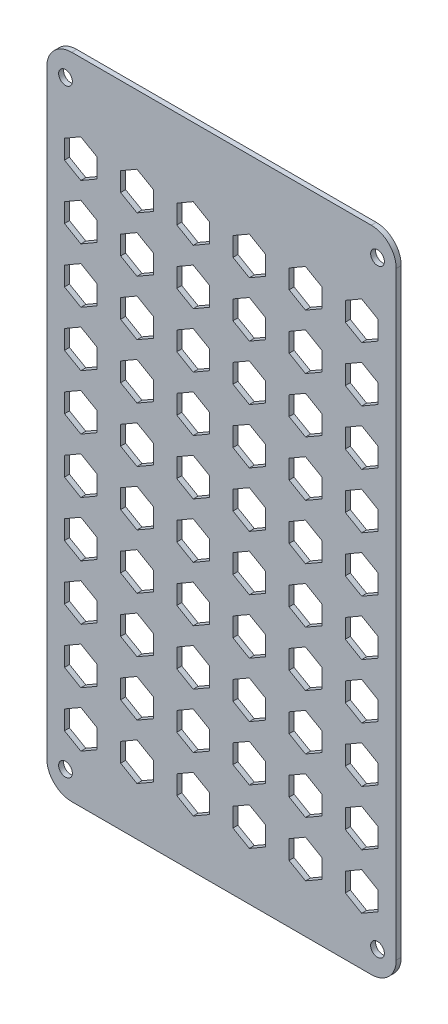
SolidWorks part; units mm, degrees
ref_plane "Front Plane" through (0, 0, 0) normal (0, 0, 1) x (1, 0, 0)
ref_plane "Top Plane" through (0, 0, 0) normal (0, 1, 0) x (1, 0, 0)
ref_plane "Right Plane" through (0, 0, 0) normal (1, 0, 0) x (0, 0, -1)
sketch "Sketch1" plane through (0, 0, 0) normal (0, 0, 1) x (1, 0, 0)
  line L1 (70, -130) -> (-70, -130)
  line L2 (70, -130) -> (70, 130)
  line L3 (70, 130) -> (-70, 130)
  line L4 (-70, -130) -> (-70, 130)
  line L5 (70, -130) -> (-70, 130) construction
  line L6 (70, 130) -> (-70, -130) construction
  point P0 (0, 0)
  dimension "D1" = 260
  dimension "D2" = 140
extrude "Boss-Extrude1" add sketch "Sketch1" along normal blind 2
sketch "Sketch2" plane through (0, 0, 2) normal (0, 0, 1) x (1, 0, 0)
  line L1 (62.5, -120) -> (-62.5, -120)
  line L2 (62.5, -120) -> (62.5, 120)
  line L3 (62.5, 120) -> (-62.5, 120)
  line L4 (-62.5, -120) -> (-62.5, 120)
  line L5 (62.5, -120) -> (-62.5, 120) construction
  line L6 (62.5, 120) -> (-62.5, -120) construction
  point P0 (0, 0)
  dimension "D1" = 125
  dimension "D2" = 240
hole_wizard "M5 Clearance Hole1" positions "3DSketch1" profile "Sketch3" hole size "M5" standard "ISO" end condition through all
sketch3d "3DSketch1"
  point P0 (-62.5, 120, 2)
  point P3 (62.5, 120, 2)
  point P6 (62.5, -120, 2)
  point P9 (-62.5, -120, 2)
sketch "Sketch3" plane through (-62.5, 120, 2) normal (1, 0, 0) x (0, -1, 0)
  line L0 (0, 0) -> (0, 2)
  line L1 (0, 2) -> (2.75, 2)
  line L2 (2.75, 2) -> (2.75, 0)
  line L5 (2.75, 0) -> (0, 0)
  line L11 (0, -6.35) -> (0, 107.95) construction
  dimension "Thru Hole Dia." = 5.5
  dimension "Thru Hole Depth" = 2
fillet "Fillet1" radius 10 4 edges at (-70, -130, 1) (70, -130, 1) (70, 130, 1) (-70, 130, 1)
sketch "Sketch4" plane through (0, 0, 2) normal (0, 0, 1) x (1, 0, 0)
  line L0 (-33.8527, 102.5023) -> (-40.4144, 98.7139)
  line L1 (-56.3527, 102.5023) -> (-62.9144, 98.7139)
  line L2 (-62.9144, 98.7139) -> (-62.9144, 91.1371)
  line L3 (-62.9144, 91.1371) -> (-56.3527, 87.3487)
  line L4 (-56.3527, 87.3487) -> (-49.791, 91.1371)
  line L5 (-49.791, 91.1371) -> (-49.791, 98.7139)
  line L6 (-49.791, 98.7139) -> (-56.3527, 102.5023)
  line L7 (-40.4144, 98.7139) -> (-40.4144, 91.1371)
  line L8 (-40.4144, 91.1371) -> (-33.8527, 87.3487)
  line L9 (-33.8527, 87.3487) -> (-27.291, 91.1371)
  line L10 (-27.291, 91.1371) -> (-27.291, 98.7139)
  line L11 (-27.291, 98.7139) -> (-33.8527, 102.5023)
  line L12 (-11.3527, 102.5023) -> (-17.9144, 98.7139)
  line L13 (-17.9144, 98.7139) -> (-17.9144, 91.1371)
  line L14 (-17.9144, 91.1371) -> (-11.3527, 87.3487)
  line L15 (-11.3527, 87.3487) -> (-4.791, 91.1371)
  line L16 (-4.791, 91.1371) -> (-4.791, 98.7139)
  line L17 (-4.791, 98.7139) -> (-11.3527, 102.5023)
  line L18 (11.1473, 102.5023) -> (4.5856, 98.7139)
  line L19 (4.5856, 98.7139) -> (4.5856, 91.1371)
  line L20 (4.5856, 91.1371) -> (11.1473, 87.3487)
  line L21 (11.1473, 87.3487) -> (17.709, 91.1371)
  line L22 (17.709, 91.1371) -> (17.709, 98.7139)
  line L23 (17.709, 98.7139) -> (11.1473, 102.5023)
  line L24 (33.6473, 102.5023) -> (27.0856, 98.7139)
  line L25 (27.0856, 98.7139) -> (27.0856, 91.1371)
  line L26 (27.0856, 91.1371) -> (33.6473, 87.3487)
  line L27 (33.6473, 87.3487) -> (40.209, 91.1371)
  line L28 (40.209, 91.1371) -> (40.209, 98.7139)
  line L29 (40.209, 98.7139) -> (33.6473, 102.5023)
  line L30 (56.1473, 102.5023) -> (49.5856, 98.7139)
  line L31 (49.5856, 98.7139) -> (49.5856, 91.1371)
  line L32 (49.5856, 91.1371) -> (56.1473, 87.3487)
  line L33 (56.1473, 87.3487) -> (62.709, 91.1371)
  line L34 (62.709, 91.1371) -> (62.709, 98.7139)
  line L35 (62.709, 98.7139) -> (56.1473, 102.5023)
  line L36 (-33.8527, 80.5023) -> (-40.4144, 76.7139)
  line L37 (-40.4144, 76.7139) -> (-40.4144, 69.1371)
  line L38 (-40.4144, 69.1371) -> (-33.8527, 65.3487)
  line L39 (-33.8527, 65.3487) -> (-27.291, 69.1371)
  line L40 (-27.291, 69.1371) -> (-27.291, 76.7139)
  line L41 (-27.291, 76.7139) -> (-33.8527, 80.5023)
  line L42 (-11.3527, 80.5023) -> (-17.9144, 76.7139)
  line L43 (-17.9144, 76.7139) -> (-17.9144, 69.1371)
  line L44 (-17.9144, 69.1371) -> (-11.3527, 65.3487)
  line L45 (-11.3527, 65.3487) -> (-4.791, 69.1371)
  line L46 (-4.791, 69.1371) -> (-4.791, 76.7139)
  line L47 (-4.791, 76.7139) -> (-11.3527, 80.5023)
  line L48 (11.1473, 80.5023) -> (4.5856, 76.7139)
  line L49 (4.5856, 76.7139) -> (4.5856, 69.1371)
  line L50 (4.5856, 69.1371) -> (11.1473, 65.3487)
  line L51 (11.1473, 65.3487) -> (17.709, 69.1371)
  line L52 (17.709, 69.1371) -> (17.709, 76.7139)
  line L53 (17.709, 76.7139) -> (11.1473, 80.5023)
  line L54 (33.6473, 80.5023) -> (27.0856, 76.7139)
  line L55 (27.0856, 76.7139) -> (27.0856, 69.1371)
  line L56 (27.0856, 69.1371) -> (33.6473, 65.3487)
  line L57 (33.6473, 65.3487) -> (40.209, 69.1371)
  line L58 (40.209, 69.1371) -> (40.209, 76.7139)
  line L59 (40.209, 76.7139) -> (33.6473, 80.5023)
  line L60 (56.1473, 80.5023) -> (49.5856, 76.7139)
  line L61 (49.5856, 76.7139) -> (49.5856, 69.1371)
  line L62 (49.5856, 69.1371) -> (56.1473, 65.3487)
  line L63 (56.1473, 65.3487) -> (62.709, 69.1371)
  line L64 (62.709, 69.1371) -> (62.709, 76.7139)
  line L65 (62.709, 76.7139) -> (56.1473, 80.5023)
  line L66 (-33.8527, 58.5023) -> (-40.4144, 54.7139)
  line L67 (-40.4144, 54.7139) -> (-40.4144, 47.1371)
  line L68 (-40.4144, 47.1371) -> (-33.8527, 43.3487)
  line L69 (-33.8527, 43.3487) -> (-27.291, 47.1371)
  line L70 (-27.291, 47.1371) -> (-27.291, 54.7139)
  line L71 (-27.291, 54.7139) -> (-33.8527, 58.5023)
  line L72 (-11.3527, 58.5023) -> (-17.9144, 54.7139)
  line L73 (-17.9144, 54.7139) -> (-17.9144, 47.1371)
  line L74 (-17.9144, 47.1371) -> (-11.3527, 43.3487)
  line L75 (-11.3527, 43.3487) -> (-4.791, 47.1371)
  line L76 (-4.791, 47.1371) -> (-4.791, 54.7139)
  line L77 (-4.791, 54.7139) -> (-11.3527, 58.5023)
  line L78 (11.1473, 58.5023) -> (4.5856, 54.7139)
  line L79 (4.5856, 54.7139) -> (4.5856, 47.1371)
  line L80 (4.5856, 47.1371) -> (11.1473, 43.3487)
  line L81 (11.1473, 43.3487) -> (17.709, 47.1371)
  line L82 (17.709, 47.1371) -> (17.709, 54.7139)
  line L83 (17.709, 54.7139) -> (11.1473, 58.5023)
  line L84 (33.6473, 58.5023) -> (27.0856, 54.7139)
  line L85 (27.0856, 54.7139) -> (27.0856, 47.1371)
  line L86 (27.0856, 47.1371) -> (33.6473, 43.3487)
  line L87 (33.6473, 43.3487) -> (40.209, 47.1371)
  line L88 (40.209, 47.1371) -> (40.209, 54.7139)
  line L89 (40.209, 54.7139) -> (33.6473, 58.5023)
  line L90 (56.1473, 58.5023) -> (49.5856, 54.7139)
  line L91 (49.5856, 54.7139) -> (49.5856, 47.1371)
  line L92 (49.5856, 47.1371) -> (56.1473, 43.3487)
  line L93 (56.1473, 43.3487) -> (62.709, 47.1371)
  line L94 (62.709, 47.1371) -> (62.709, 54.7139)
  line L95 (62.709, 54.7139) -> (56.1473, 58.5023)
  line L96 (-33.8527, 36.5023) -> (-40.4144, 32.7139)
  line L97 (-40.4144, 32.7139) -> (-40.4144, 25.1371)
  line L98 (-40.4144, 25.1371) -> (-33.8527, 21.3487)
  line L99 (-33.8527, 21.3487) -> (-27.291, 25.1371)
  line L100 (-27.291, 25.1371) -> (-27.291, 32.7139)
  line L101 (-27.291, 32.7139) -> (-33.8527, 36.5023)
  line L102 (-11.3527, 36.5023) -> (-17.9144, 32.7139)
  line L103 (-17.9144, 32.7139) -> (-17.9144, 25.1371)
  line L104 (-17.9144, 25.1371) -> (-11.3527, 21.3487)
  line L105 (-11.3527, 21.3487) -> (-4.791, 25.1371)
  line L106 (-4.791, 25.1371) -> (-4.791, 32.7139)
  line L107 (-4.791, 32.7139) -> (-11.3527, 36.5023)
  line L108 (11.1473, 36.5023) -> (4.5856, 32.7139)
  line L109 (4.5856, 32.7139) -> (4.5856, 25.1371)
  line L110 (4.5856, 25.1371) -> (11.1473, 21.3487)
  line L111 (11.1473, 21.3487) -> (17.709, 25.1371)
  line L112 (17.709, 25.1371) -> (17.709, 32.7139)
  line L113 (17.709, 32.7139) -> (11.1473, 36.5023)
  line L114 (33.6473, 36.5023) -> (27.0856, 32.7139)
  line L115 (27.0856, 32.7139) -> (27.0856, 25.1371)
  line L116 (27.0856, 25.1371) -> (33.6473, 21.3487)
  line L117 (33.6473, 21.3487) -> (40.209, 25.1371)
  line L118 (40.209, 25.1371) -> (40.209, 32.7139)
  line L119 (40.209, 32.7139) -> (33.6473, 36.5023)
  line L120 (56.1473, 36.5023) -> (49.5856, 32.7139)
  line L121 (49.5856, 32.7139) -> (49.5856, 25.1371)
  line L122 (49.5856, 25.1371) -> (56.1473, 21.3487)
  line L123 (56.1473, 21.3487) -> (62.709, 25.1371)
  line L124 (62.709, 25.1371) -> (62.709, 32.7139)
  line L125 (62.709, 32.7139) -> (56.1473, 36.5023)
  line L126 (-33.8527, 14.5023) -> (-40.4144, 10.7139)
  line L127 (-40.4144, 10.7139) -> (-40.4144, 3.1371)
  line L128 (-40.4144, 3.1371) -> (-33.8527, -0.6513)
  line L129 (-33.8527, -0.6513) -> (-27.291, 3.1371)
  line L130 (-27.291, 3.1371) -> (-27.291, 10.7139)
  line L131 (-27.291, 10.7139) -> (-33.8527, 14.5023)
  line L132 (-11.3527, 14.5023) -> (-17.9144, 10.7139)
  line L133 (-17.9144, 10.7139) -> (-17.9144, 3.1371)
  line L134 (-17.9144, 3.1371) -> (-11.3527, -0.6513)
  line L135 (-11.3527, -0.6513) -> (-4.791, 3.1371)
  line L136 (-4.791, 3.1371) -> (-4.791, 10.7139)
  line L137 (-4.791, 10.7139) -> (-11.3527, 14.5023)
  line L138 (11.1473, 14.5023) -> (4.5856, 10.7139)
  line L139 (4.5856, 10.7139) -> (4.5856, 3.1371)
  line L140 (4.5856, 3.1371) -> (11.1473, -0.6513)
  line L141 (11.1473, -0.6513) -> (17.709, 3.1371)
  line L142 (17.709, 3.1371) -> (17.709, 10.7139)
  line L143 (17.709, 10.7139) -> (11.1473, 14.5023)
  line L144 (33.6473, 14.5023) -> (27.0856, 10.7139)
  line L145 (27.0856, 10.7139) -> (27.0856, 3.1371)
  line L146 (27.0856, 3.1371) -> (33.6473, -0.6513)
  line L147 (33.6473, -0.6513) -> (40.209, 3.1371)
  line L148 (40.209, 3.1371) -> (40.209, 10.7139)
  line L149 (40.209, 10.7139) -> (33.6473, 14.5023)
  line L150 (56.1473, 14.5023) -> (49.5856, 10.7139)
  line L151 (49.5856, 10.7139) -> (49.5856, 3.1371)
  line L152 (49.5856, 3.1371) -> (56.1473, -0.6513)
  line L153 (56.1473, -0.6513) -> (62.709, 3.1371)
  line L154 (62.709, 3.1371) -> (62.709, 10.7139)
  line L155 (62.709, 10.7139) -> (56.1473, 14.5023)
  line L156 (-33.8527, -7.4977) -> (-40.4144, -11.2861)
  line L157 (-40.4144, -11.2861) -> (-40.4144, -18.8629)
  line L158 (-40.4144, -18.8629) -> (-33.8527, -22.6513)
  line L159 (-33.8527, -22.6513) -> (-27.291, -18.8629)
  line L160 (-27.291, -18.8629) -> (-27.291, -11.2861)
  line L161 (-27.291, -11.2861) -> (-33.8527, -7.4977)
  line L162 (-11.3527, -7.4977) -> (-17.9144, -11.2861)
  line L163 (-17.9144, -11.2861) -> (-17.9144, -18.8629)
  line L164 (-17.9144, -18.8629) -> (-11.3527, -22.6513)
  line L165 (-11.3527, -22.6513) -> (-4.791, -18.8629)
  line L166 (-4.791, -18.8629) -> (-4.791, -11.2861)
  line L167 (-4.791, -11.2861) -> (-11.3527, -7.4977)
  line L168 (11.1473, -7.4977) -> (4.5856, -11.2861)
  line L169 (4.5856, -11.2861) -> (4.5856, -18.8629)
  line L170 (4.5856, -18.8629) -> (11.1473, -22.6513)
  line L171 (11.1473, -22.6513) -> (17.709, -18.8629)
  line L172 (17.709, -18.8629) -> (17.709, -11.2861)
  line L173 (17.709, -11.2861) -> (11.1473, -7.4977)
  line L174 (33.6473, -7.4977) -> (27.0856, -11.2861)
  line L175 (27.0856, -11.2861) -> (27.0856, -18.8629)
  line L176 (27.0856, -18.8629) -> (33.6473, -22.6513)
  line L177 (33.6473, -22.6513) -> (40.209, -18.8629)
  line L178 (40.209, -18.8629) -> (40.209, -11.2861)
  line L179 (40.209, -11.2861) -> (33.6473, -7.4977)
  line L180 (56.1473, -7.4977) -> (49.5856, -11.2861)
  line L181 (49.5856, -11.2861) -> (49.5856, -18.8629)
  line L182 (49.5856, -18.8629) -> (56.1473, -22.6513)
  line L183 (56.1473, -22.6513) -> (62.709, -18.8629)
  line L184 (62.709, -18.8629) -> (62.709, -11.2861)
  line L185 (62.709, -11.2861) -> (56.1473, -7.4977)
  line L186 (-33.8527, -29.4977) -> (-40.4144, -33.2861)
  line L187 (-40.4144, -33.2861) -> (-40.4144, -40.8629)
  line L188 (-40.4144, -40.8629) -> (-33.8527, -44.6513)
  line L189 (-33.8527, -44.6513) -> (-27.291, -40.8629)
  line L190 (-27.291, -40.8629) -> (-27.291, -33.2861)
  line L191 (-27.291, -33.2861) -> (-33.8527, -29.4977)
  line L192 (-11.3527, -29.4977) -> (-17.9144, -33.2861)
  line L193 (-17.9144, -33.2861) -> (-17.9144, -40.8629)
  line L194 (-17.9144, -40.8629) -> (-11.3527, -44.6513)
  line L195 (-11.3527, -44.6513) -> (-4.791, -40.8629)
  line L196 (-4.791, -40.8629) -> (-4.791, -33.2861)
  line L197 (-4.791, -33.2861) -> (-11.3527, -29.4977)
  line L198 (11.1473, -29.4977) -> (4.5856, -33.2861)
  line L199 (4.5856, -33.2861) -> (4.5856, -40.8629)
  line L200 (4.5856, -40.8629) -> (11.1473, -44.6513)
  line L201 (11.1473, -44.6513) -> (17.709, -40.8629)
  line L202 (17.709, -40.8629) -> (17.709, -33.2861)
  line L203 (17.709, -33.2861) -> (11.1473, -29.4977)
  line L204 (33.6473, -29.4977) -> (27.0856, -33.2861)
  line L205 (27.0856, -33.2861) -> (27.0856, -40.8629)
  line L206 (27.0856, -40.8629) -> (33.6473, -44.6513)
  line L207 (33.6473, -44.6513) -> (40.209, -40.8629)
  line L208 (40.209, -40.8629) -> (40.209, -33.2861)
  line L209 (40.209, -33.2861) -> (33.6473, -29.4977)
  line L210 (56.1473, -29.4977) -> (49.5856, -33.2861)
  line L211 (49.5856, -33.2861) -> (49.5856, -40.8629)
  line L212 (49.5856, -40.8629) -> (56.1473, -44.6513)
  line L213 (56.1473, -44.6513) -> (62.709, -40.8629)
  line L214 (62.709, -40.8629) -> (62.709, -33.2861)
  line L215 (62.709, -33.2861) -> (56.1473, -29.4977)
  line L216 (-33.8527, -51.4977) -> (-40.4144, -55.2861)
  line L217 (-40.4144, -55.2861) -> (-40.4144, -62.8629)
  line L218 (-40.4144, -62.8629) -> (-33.8527, -66.6513)
  line L219 (-33.8527, -66.6513) -> (-27.291, -62.8629)
  line L220 (-27.291, -62.8629) -> (-27.291, -55.2861)
  line L221 (-27.291, -55.2861) -> (-33.8527, -51.4977)
  line L222 (-11.3527, -51.4977) -> (-17.9144, -55.2861)
  line L223 (-17.9144, -55.2861) -> (-17.9144, -62.8629)
  line L224 (-17.9144, -62.8629) -> (-11.3527, -66.6513)
  line L225 (-11.3527, -66.6513) -> (-4.791, -62.8629)
  line L226 (-4.791, -62.8629) -> (-4.791, -55.2861)
  line L227 (-4.791, -55.2861) -> (-11.3527, -51.4977)
  line L228 (11.1473, -51.4977) -> (4.5856, -55.2861)
  line L229 (4.5856, -55.2861) -> (4.5856, -62.8629)
  line L230 (4.5856, -62.8629) -> (11.1473, -66.6513)
  line L231 (11.1473, -66.6513) -> (17.709, -62.8629)
  line L232 (17.709, -62.8629) -> (17.709, -55.2861)
  line L233 (17.709, -55.2861) -> (11.1473, -51.4977)
  line L234 (33.6473, -51.4977) -> (27.0856, -55.2861)
  line L235 (27.0856, -55.2861) -> (27.0856, -62.8629)
  line L236 (27.0856, -62.8629) -> (33.6473, -66.6513)
  line L237 (33.6473, -66.6513) -> (40.209, -62.8629)
  line L238 (40.209, -62.8629) -> (40.209, -55.2861)
  line L239 (40.209, -55.2861) -> (33.6473, -51.4977)
  line L240 (56.1473, -51.4977) -> (49.5856, -55.2861)
  line L241 (49.5856, -55.2861) -> (49.5856, -62.8629)
  line L242 (49.5856, -62.8629) -> (56.1473, -66.6513)
  line L243 (56.1473, -66.6513) -> (62.709, -62.8629)
  line L244 (62.709, -62.8629) -> (62.709, -55.2861)
  line L245 (62.709, -55.2861) -> (56.1473, -51.4977)
  line L246 (-33.8527, -73.4977) -> (-40.4144, -77.2861)
  line L247 (-40.4144, -77.2861) -> (-40.4144, -84.8629)
  line L248 (-40.4144, -84.8629) -> (-33.8527, -88.6513)
  line L249 (-33.8527, -88.6513) -> (-27.291, -84.8629)
  line L250 (-27.291, -84.8629) -> (-27.291, -77.2861)
  line L251 (-27.291, -77.2861) -> (-33.8527, -73.4977)
  line L252 (-11.3527, -73.4977) -> (-17.9144, -77.2861)
  line L253 (-17.9144, -77.2861) -> (-17.9144, -84.8629)
  line L254 (-17.9144, -84.8629) -> (-11.3527, -88.6513)
  line L255 (-11.3527, -88.6513) -> (-4.791, -84.8629)
  line L256 (-4.791, -84.8629) -> (-4.791, -77.2861)
  line L257 (-4.791, -77.2861) -> (-11.3527, -73.4977)
  line L258 (11.1473, -73.4977) -> (4.5856, -77.2861)
  line L259 (4.5856, -77.2861) -> (4.5856, -84.8629)
  line L260 (4.5856, -84.8629) -> (11.1473, -88.6513)
  line L261 (11.1473, -88.6513) -> (17.709, -84.8629)
  line L262 (17.709, -84.8629) -> (17.709, -77.2861)
  line L263 (17.709, -77.2861) -> (11.1473, -73.4977)
  line L264 (33.6473, -73.4977) -> (27.0856, -77.2861)
  line L265 (27.0856, -77.2861) -> (27.0856, -84.8629)
  line L266 (27.0856, -84.8629) -> (33.6473, -88.6513)
  line L267 (33.6473, -88.6513) -> (40.209, -84.8629)
  line L268 (40.209, -84.8629) -> (40.209, -77.2861)
  line L269 (40.209, -77.2861) -> (33.6473, -73.4977)
  line L270 (56.1473, -73.4977) -> (49.5856, -77.2861)
  line L271 (49.5856, -77.2861) -> (49.5856, -84.8629)
  line L272 (49.5856, -84.8629) -> (56.1473, -88.6513)
  line L273 (56.1473, -88.6513) -> (62.709, -84.8629)
  line L274 (62.709, -84.8629) -> (62.709, -77.2861)
  line L275 (62.709, -77.2861) -> (56.1473, -73.4977)
  line L276 (-33.8527, -95.4977) -> (-40.4144, -99.2861)
  line L277 (-40.4144, -99.2861) -> (-40.4144, -106.8629)
  line L278 (-40.4144, -106.8629) -> (-33.8527, -110.6513)
  line L279 (-33.8527, -110.6513) -> (-27.291, -106.8629)
  line L280 (-27.291, -106.8629) -> (-27.291, -99.2861)
  line L281 (-27.291, -99.2861) -> (-33.8527, -95.4977)
  line L282 (-11.3527, -95.4977) -> (-17.9144, -99.2861)
  line L283 (-17.9144, -99.2861) -> (-17.9144, -106.8629)
  line L284 (-17.9144, -106.8629) -> (-11.3527, -110.6513)
  line L285 (-11.3527, -110.6513) -> (-4.791, -106.8629)
  line L286 (-4.791, -106.8629) -> (-4.791, -99.2861)
  line L287 (-4.791, -99.2861) -> (-11.3527, -95.4977)
  line L288 (11.1473, -95.4977) -> (4.5856, -99.2861)
  line L289 (4.5856, -99.2861) -> (4.5856, -106.8629)
  line L290 (4.5856, -106.8629) -> (11.1473, -110.6513)
  line L291 (11.1473, -110.6513) -> (17.709, -106.8629)
  line L292 (17.709, -106.8629) -> (17.709, -99.2861)
  line L293 (17.709, -99.2861) -> (11.1473, -95.4977)
  line L294 (33.6473, -95.4977) -> (27.0856, -99.2861)
  line L295 (27.0856, -99.2861) -> (27.0856, -106.8629)
  line L296 (27.0856, -106.8629) -> (33.6473, -110.6513)
  line L297 (33.6473, -110.6513) -> (40.209, -106.8629)
  line L298 (40.209, -106.8629) -> (40.209, -99.2861)
  line L299 (40.209, -99.2861) -> (33.6473, -95.4977)
  line L300 (56.1473, -95.4977) -> (49.5856, -99.2861)
  line L301 (49.5856, -99.2861) -> (49.5856, -106.8629)
  line L302 (49.5856, -106.8629) -> (56.1473, -110.6513)
  line L303 (56.1473, -110.6513) -> (62.709, -106.8629)
  line L304 (62.709, -106.8629) -> (62.709, -99.2861)
  line L305 (62.709, -99.2861) -> (56.1473, -95.4977)
  line L306 (-56.3527, 80.5023) -> (-62.9144, 76.7139)
  line L307 (-62.9144, 76.7139) -> (-62.9144, 69.1371)
  line L308 (-62.9144, 69.1371) -> (-56.3527, 65.3487)
  line L309 (-56.3527, 65.3487) -> (-49.791, 69.1371)
  line L310 (-49.791, 69.1371) -> (-49.791, 76.7139)
  line L311 (-49.791, 76.7139) -> (-56.3527, 80.5023)
  line L312 (-56.3527, 58.5023) -> (-62.9144, 54.7139)
  line L313 (-62.9144, 54.7139) -> (-62.9144, 47.1371)
  line L314 (-62.9144, 47.1371) -> (-56.3527, 43.3487)
  line L315 (-56.3527, 43.3487) -> (-49.791, 47.1371)
  line L316 (-49.791, 47.1371) -> (-49.791, 54.7139)
  line L317 (-49.791, 54.7139) -> (-56.3527, 58.5023)
  line L318 (-56.3527, 36.5023) -> (-62.9144, 32.7139)
  line L319 (-62.9144, 32.7139) -> (-62.9144, 25.1371)
  line L320 (-62.9144, 25.1371) -> (-56.3527, 21.3487)
  line L321 (-56.3527, 21.3487) -> (-49.791, 25.1371)
  line L322 (-49.791, 25.1371) -> (-49.791, 32.7139)
  line L323 (-49.791, 32.7139) -> (-56.3527, 36.5023)
  line L324 (-56.3527, 14.5023) -> (-62.9144, 10.7139)
  line L325 (-62.9144, 10.7139) -> (-62.9144, 3.1371)
  line L326 (-62.9144, 3.1371) -> (-56.3527, -0.6513)
  line L327 (-56.3527, -0.6513) -> (-49.791, 3.1371)
  line L328 (-49.791, 3.1371) -> (-49.791, 10.7139)
  line L329 (-49.791, 10.7139) -> (-56.3527, 14.5023)
  line L330 (-56.3527, -7.4977) -> (-62.9144, -11.2861)
  line L331 (-62.9144, -11.2861) -> (-62.9144, -18.8629)
  line L332 (-62.9144, -18.8629) -> (-56.3527, -22.6513)
  line L333 (-56.3527, -22.6513) -> (-49.791, -18.8629)
  line L334 (-49.791, -18.8629) -> (-49.791, -11.2861)
  line L335 (-49.791, -11.2861) -> (-56.3527, -7.4977)
  line L336 (-56.3527, -29.4977) -> (-62.9144, -33.2861)
  line L337 (-62.9144, -33.2861) -> (-62.9144, -40.8629)
  line L338 (-62.9144, -40.8629) -> (-56.3527, -44.6513)
  line L339 (-56.3527, -44.6513) -> (-49.791, -40.8629)
  line L340 (-49.791, -40.8629) -> (-49.791, -33.2861)
  line L341 (-49.791, -33.2861) -> (-56.3527, -29.4977)
  line L342 (-56.3527, -51.4977) -> (-62.9144, -55.2861)
  line L343 (-62.9144, -55.2861) -> (-62.9144, -62.8629)
  line L344 (-62.9144, -62.8629) -> (-56.3527, -66.6513)
  line L345 (-56.3527, -66.6513) -> (-49.791, -62.8629)
  line L346 (-49.791, -62.8629) -> (-49.791, -55.2861)
  line L347 (-49.791, -55.2861) -> (-56.3527, -51.4977)
  line L348 (-56.3527, -73.4977) -> (-62.9144, -77.2861)
  line L349 (-62.9144, -77.2861) -> (-62.9144, -84.8629)
  line L350 (-62.9144, -84.8629) -> (-56.3527, -88.6513)
  line L351 (-56.3527, -88.6513) -> (-49.791, -84.8629)
  line L352 (-49.791, -84.8629) -> (-49.791, -77.2861)
  line L353 (-49.791, -77.2861) -> (-56.3527, -73.4977)
  line L354 (-56.3527, -95.4977) -> (-62.9144, -99.2861)
  line L355 (-62.9144, -99.2861) -> (-62.9144, -106.8629)
  line L356 (-62.9144, -106.8629) -> (-56.3527, -110.6513)
  line L357 (-56.3527, -110.6513) -> (-49.791, -106.8629)
  line L358 (-49.791, -106.8629) -> (-49.791, -99.2861)
  line L359 (-49.791, -99.2861) -> (-56.3527, -95.4977)
  circle A0 centre (-56.3527, 94.9255) radius 6.5617 construction
  dimension "D1" = 6
  dimension "D2" = 10
extrude "Cut-Extrude1" cut sketch "Sketch4" against normal blind 2
